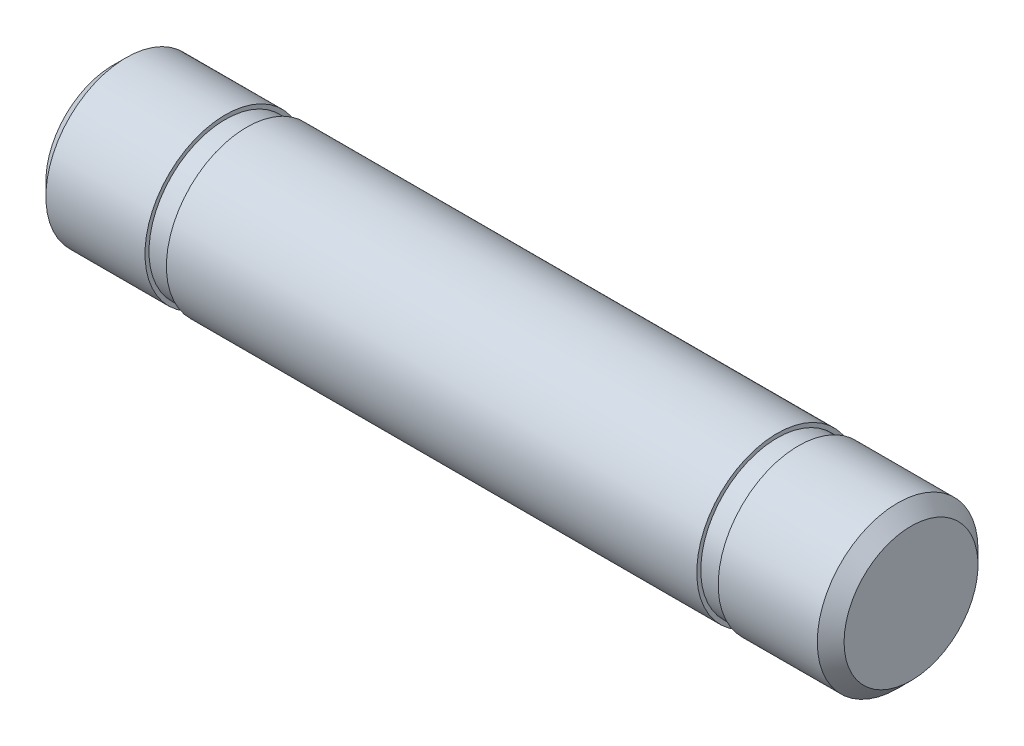
SolidWorks part; units mm, degrees
ref_plane "Alzado" through (0, 0, 0) normal (1, 0, 0) x (0, 1, 0)
ref_plane "Planta" through (0, 0, 0) normal (0, 0, 1) x (0, 1, 0)
ref_plane "Vista lateral" through (0, 0, 0) normal (0, 1, 0) x (-1, 0, 0)
sketch "Croquis1" plane through (0, 0, 0) normal (0, 1, 0) x (-1, 0, 0)
  line L1 (-9.9, 3) -> (9.9, 3)
  line L6 (14.9, 3) -> (14.9, 0)
  line L7 (-14.9, 0) -> (14.9, 0) construction
  line L23 (9.9, 3) -> (9.9, 2.85)
  line L24 (9.9, 2.85) -> (10.7, 2.85)
  line L25 (10.7, 2.85) -> (10.7, 3)
  line L26 (10.7, 3) -> (14.9, 3)
  line L27 (0, 0) -> (0, 3) construction
  line L28 (-10.7, 3) -> (-14.9, 3)
  line L29 (-10.7, 2.85) -> (-10.7, 3)
  line L30 (-9.9, 2.85) -> (-10.7, 2.85)
  line L31 (-9.9, 3) -> (-9.9, 2.85)
  line L32 (-14.9, 3) -> (-14.9, 0)
  line L33 (-14.9, 0) -> (14.9, 0)
  dimension "D1" = 5
  dimension "D2" = 6
  dimension "D3" = 19.8
  dimension "D4" = 5.7
  dimension "D5" = 0.8
revolve "Revolución1" add sketch "Croquis1" angle 360 about L7
chamfer "Chaflán1" distance 0.5 angle 45 2 edges at (14.9, 0, -3) (-14.9, 0, -3)
equation "\"ancho_circlip\"=0.8"
equation "\"ranura_circlip\"=0.45"
